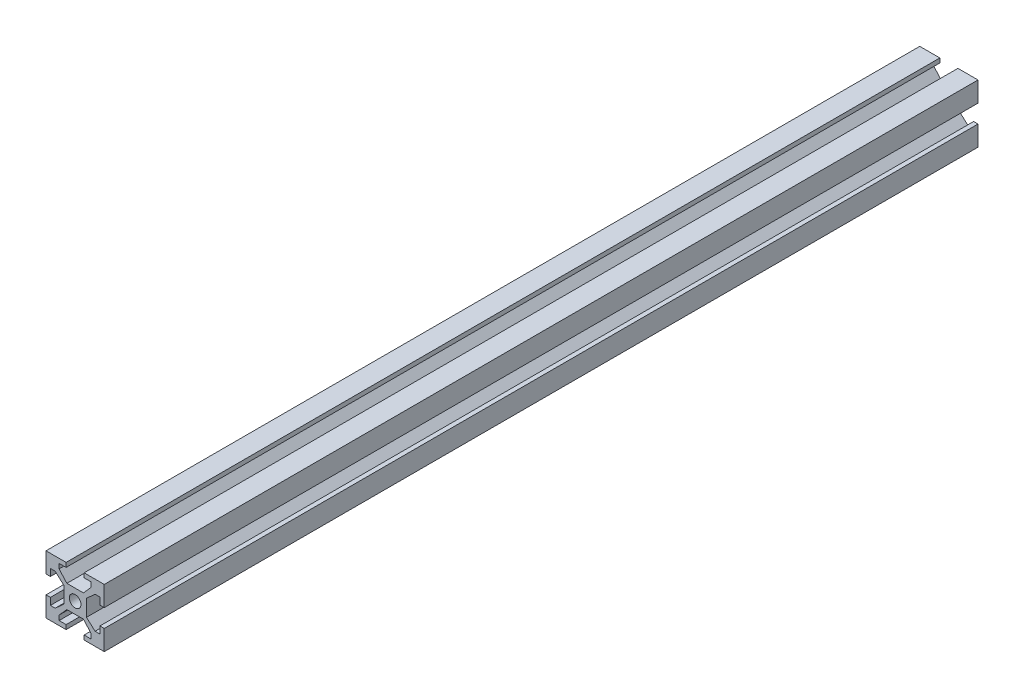
SolidWorks part; units mm, degrees
material "6063-T6"
ref_plane "Front Plane" through (0, 0, 0) normal (0, 0, 1) x (1, 0, 0)
ref_plane "Top Plane" through (0, 0, 0) normal (0, 1, 0) x (1, 0, 0)
ref_plane "Right Plane" through (0, 0, 0) normal (1, 0, 0) x (0, 0, -1)
sketch "Sketch1" plane through (0, 0, 0) normal (0, 0, 1) x (1, 0, 0)
  line L0 (10, 10) -> (4.6104, 10) construction
  line L1 (10, 10) -> (10, 4.6104) construction
  line L2 (10, -10) -> (10, -4.6104) construction
  line L3 (10, -10) -> (4.6104, -10) construction
  line L4 (10, 10) -> (10, 4.6104)
  line L5 (6.8607, 5.5) -> (8.5, 5.5)
  line L6 (5.5, 8.5) -> (5.5, 6.8607)
  line L7 (10, 10) -> (4.6104, 10)
  line L8 (10, 10) -> (10, 4.6104)
  line L9 (6.8607, 5.5) -> (3.9, 2.8393)
  line L10 (5.5, 6.8607) -> (2.8393, 3.9)
  line L13 (8.5, 3.1) -> (8.5, 5.5)
  line L14 (3.1, 8.5) -> (5.5, 8.5)
  line L15 (-6.8607, 5.5) -> (-8.5, 5.5)
  line L16 (6.8607, -5.5) -> (8.5, -5.5)
  line L17 (3.1, -8.5) -> (5.5, -8.5)
  line L18 (8.5, -3.1) -> (8.5, -5.5)
  line L19 (8.5, -3.1) -> (10, -3.1)
  line L20 (8.5, 3.1) -> (10, 3.1)
  line L21 (-3.9, 0.5196) -> (-3.9, -0.5196)
  line L22 (-0.5196, 3.9) -> (0.5196, 3.9)
  line L23 (3.9, 0.5196) -> (3.9, -0.5196)
  line L24 (-0.5196, -3.9) -> (0.5196, -3.9)
  line L25 (3.9, 0.5196) -> (3.9, 2.8393)
  line L26 (2.8393, 3.9) -> (0.5196, 3.9)
  line L27 (3.9, -2.8393) -> (3.9, -0.5196)
  line L28 (2.8393, -3.9) -> (0.5196, -3.9)
  line L29 (5.5, -6.8607) -> (2.8393, -3.9)
  line L30 (6.8607, -5.5) -> (3.9, -2.8393)
  line L31 (10, -10) -> (10, -4.6104)
  line L32 (10, -10) -> (4.6104, -10)
  line L33 (5.5, -8.5) -> (5.5, -6.8607)
  line L34 (-6.8607, -5.5) -> (-8.5, -5.5)
  line L35 (10, -10) -> (10, -4.6104)
  line L36 (0, 0) -> (0, 8.5) construction
  line L37 (-10, -10) -> (-4.6104, -10) construction
  line L38 (-10, -10) -> (-10, -4.6104) construction
  line L39 (-10, 10) -> (-10, 4.6104) construction
  line L40 (-10, 10) -> (-4.6104, 10) construction
  line L41 (-10, -10) -> (-10, -4.6104)
  line L42 (-3.1, -8.5) -> (-3.1, -10)
  line L43 (-5.5, -8.5) -> (-5.5, -6.8607)
  line L44 (-10, -10) -> (-4.6104, -10)
  line L45 (-10, -10) -> (-10, -4.6104)
  line L46 (-6.8607, -5.5) -> (-3.9, -2.8393)
  line L47 (-5.5, -6.8607) -> (-2.8393, -3.9)
  line L48 (-2.8393, -3.9) -> (-0.5196, -3.9)
  line L49 (-3.9, -2.8393) -> (-3.9, -0.5196)
  line L50 (-2.8393, 3.9) -> (-0.5196, 3.9)
  line L51 (-3.9, 0.5196) -> (-3.9, 2.8393)
  line L52 (-3.1, -10) -> (-4.6104, -10)
  line L53 (3.1, -8.5) -> (3.1, -10)
  line L54 (3.1, -10) -> (4.6104, -10)
  line L55 (10, -3.1) -> (10, -4.6104)
  line L57 (10, 3.1) -> (10, 4.6104)
  line L58 (-8.5, -3.1) -> (-8.5, -5.5)
  line L59 (-3.1, -8.5) -> (-5.5, -8.5)
  line L60 (-10, -10) -> (10, -10) construction
  line L61 (-10, -10) -> (-10, 10) construction
  line L62 (-3.1, 8.5) -> (-5.5, 8.5)
  line L63 (-8.5, 3.1) -> (-8.5, 5.5)
  line L66 (-5.5, 6.8607) -> (-2.8393, 3.9)
  line L67 (-6.8607, 5.5) -> (-3.9, 2.8393)
  line L68 (-10, 10) -> (-10, 4.6104)
  line L69 (-10, 10) -> (-4.6104, 10)
  line L70 (-5.5, 8.5) -> (-5.5, 6.8607)
  line L71 (-10, 10) -> (10, 10) construction
  line L72 (-10, 10) -> (-10, 4.6104)
  line L73 (10, -10) -> (10, 10) construction
  line L74 (-10, -10) -> (10, 10) construction
  line L75 (-10, 10) -> (10, -10) construction
  line L76 (3.1, 8.5) -> (3.1, 10)
  line L77 (3.1, 10) -> (4.6104, 10)
  line L78 (-3.1, 8.5) -> (-3.1, 10)
  line L79 (-3.1, 10) -> (-4.6104, 10)
  line L80 (-8.5, 3.1) -> (-10, 3.1)
  line L81 (-10, 3.1) -> (-10, 4.6104)
  line L82 (-8.5, -3.1) -> (-10, -3.1)
  line L83 (-10, -3.1) -> (-10, -4.6104)
  circle A0 centre (0, 0) radius 2
  dimension "D7" = 4
  dimension "D1" = 20
  dimension "D2" = 5.3896
  dimension "D3" = 4.5
  dimension "D5" = 1.5
  dimension "D6" = 1.5104
  dimension "D8" = 5.5
  dimension "D11" = 2.3197
  dimension "D12" = 7.8
  dimension "D13" = 7.8
  dimension "D14" = 1.5
  dimension "D15" = 2.6607
extrude "Boss-Extrude1" add sketch "Sketch1" along normal mid plane 300
